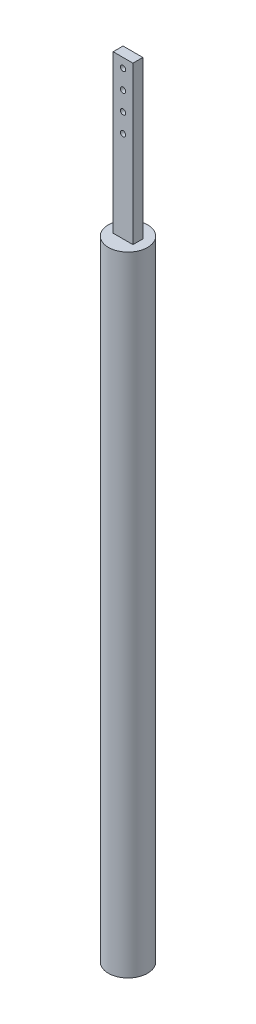
SolidWorks part; units mm, degrees
ref_plane "Front Plane" through (0, 0, 0) normal (0, 0, 1) x (1, 0, 0)
ref_plane "Top Plane" through (0, 0, 0) normal (0, 1, 0) x (1, 0, 0)
ref_plane "Right Plane" through (0, 0, 0) normal (1, 0, 0) x (0, 0, -1)
sketch "Sketch1" plane through (0, 0, 0) normal (0, 1, 0) x (1, 0, 0)
  circle A0 centre (0, 0) radius 3.9624
  dimension "D1" = 3.9624
extrude "Boss-Extrude1" add sketch "Sketch1" along normal blind 127 contours A0
sketch "Sketch4" plane through (0, 127, 0) normal (0, 1, 0) x (1, 0, 0)
  line L0 (-2, 1) -> (-2, -1)
  line L1 (-2, -1) -> (2, -1)
  line L2 (2, -1) -> (2, 1)
  line L3 (2, 1) -> (-2, 1)
  point P0 (0, 0)
  dimension "D1" = 4
  dimension "D2" = 1
  dimension "D3" = 1
extrude "Boss-Extrude2" add sketch "Sketch4" along normal blind 31.75
sketch "Sketch5" plane through (0, 0, -1) normal (0, 0, -1) x (-1, 0, 0)
  line L2 (-2, 158.75) -> (2, 158.75) construction
  circle A0 centre (0, 156.845) radius 0.5334
  circle A1 centre (0, 153.035) radius 0.5334
  circle A2 centre (0, 149.225) radius 0.5334
  circle A3 centre (0, 145.415) radius 0.5334
  point P5 (0, 158.75)
  dimension "D1" = 1.0668
  dimension "D3" = 1.905
  dimension "D2" = 4
  dimension "D4" = 3.81
extrude "Cut-Extrude1" cut sketch "Sketch5" against normal blind 2 contours A1 | A2 | A3
